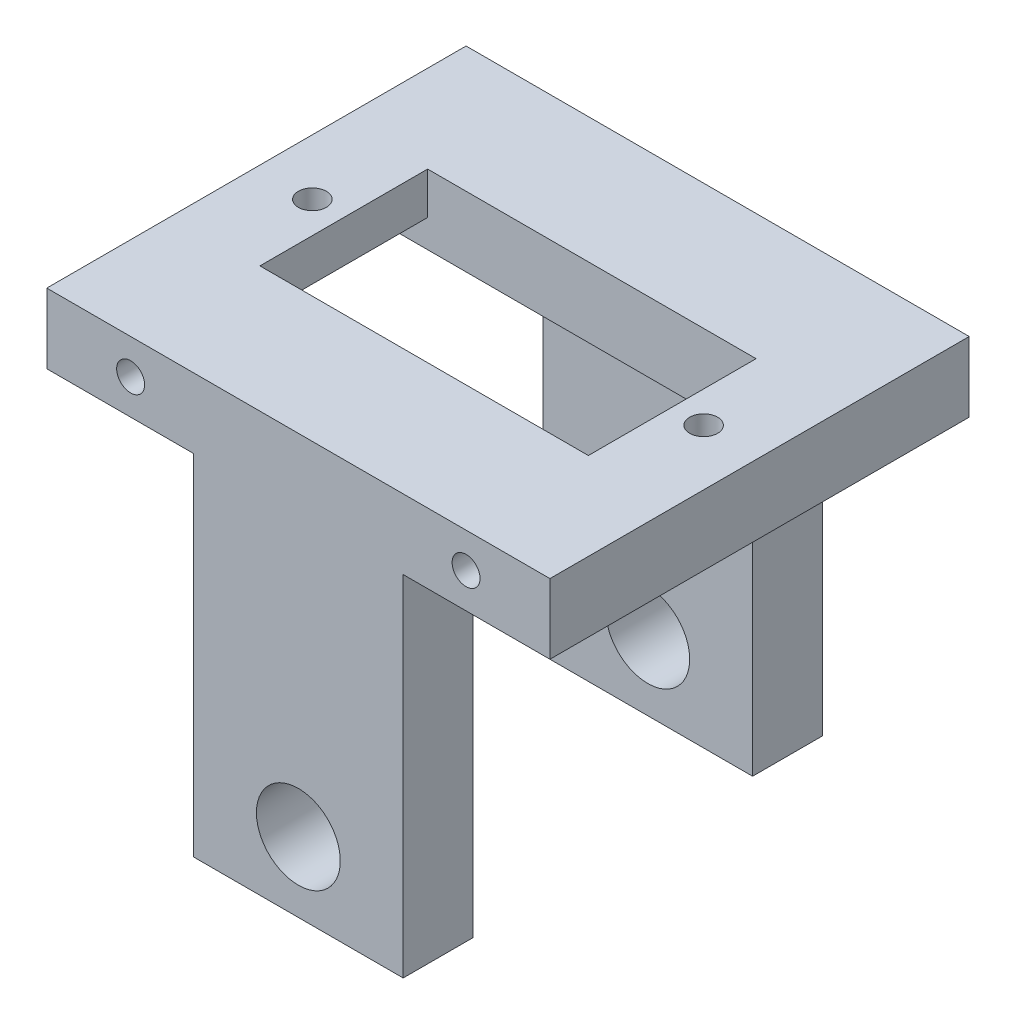
SolidWorks part; units mm, degrees
ref_plane "前视基准面" through (0, 0, 0) normal (0, 0, 1) x (1, 0, 0)
ref_plane "上视基准面" through (0, 0, 0) normal (0, 1, 0) x (1, 0, 0)
ref_plane "右视基准面" through (0, 0, 0) normal (1, 0, 0) x (0, 0, -1)
sketch "草图1" plane through (0, 0, 0) normal (0, 1, 0) x (1, 0, 0)
  line L1 (-18, 15) -> (18, 15)
  line L2 (-18, 15) -> (-18, -15)
  line L3 (-18, -15) -> (18, -15)
  line L4 (18, 15) -> (18, -15)
  line L5 (-18, 15) -> (18, -15) construction
  line L6 (-18, -15) -> (18, 15) construction
  point P0 (0, 0)
  dimension "D1" = 30
  dimension "D2" = 36
extrude "凸台-拉伸1" add sketch "草图1" along normal blind 5
sketch "草图4" plane through (0, 0, 0) normal (0, -1, 0) x (1, 0, 0)
  line L1 (-16.5, 6) -> (16.5, 6)
  line L2 (-16.5, 6) -> (-16.5, -6)
  line L3 (-16.5, -6) -> (16.5, -6)
  line L4 (16.5, 6) -> (16.5, -6)
  line L5 (-16.5, 6) -> (16.5, -6) construction
  line L6 (-16.5, -6) -> (16.5, 6) construction
  point P0 (0, 0)
  dimension "D1" = 33
  dimension "D2" = 12
extrude "切除-拉伸2" cut sketch "草图4" against normal blind 2
sketch "草图8" plane through (0, 2, 0) normal (0, -1, 0) x (1, 0, 0)
  line L0 (0, -1000) -> (0, 49000) construction
  circle A0 centre (14, 0) radius 1
  circle A1 centre (-14, 0) radius 1
  dimension "D1" = 28
  dimension "D2" = 2
extrude "切除-拉伸6" cut sketch "草图8" against normal blind 3
sketch "草图5" plane through (0, 2, 0) normal (0, -1, 0) x (1, 0, 0)
  line L0 (16.5, 6) -> (-16.5, 6) construction
  line L1 (-11.75, -6) -> (11.75, -6)
  line L2 (-11.75, -6) -> (-11.75, 6)
  line L3 (-11.75, 6) -> (11.75, 6)
  line L4 (11.75, -6) -> (11.75, 6)
  line L5 (-11.75, -6) -> (11.75, 6) construction
  line L6 (-11.75, 6) -> (11.75, -6) construction
  point P0 (0, 0)
  dimension "D1" = 23.5
extrude "切除-拉伸3" cut sketch "草图5" against normal up to surface (3 mm away) and the other way through all up to face at (-14, 5, -1)
sketch "草图9" plane through (0, 0, -15) normal (0, 0, -1) x (-1, 0, 0)
  line L0 (-1000, 2.5) -> (49000, 2.5) construction
  line L2 (-18, 5) -> (18, 0) construction
  line L3 (18, 5) -> (-18, 0) construction
  line L4 (0, -997.25) -> (0, 49002.75) construction
  circle A0 centre (12, 2.5) radius 1
  circle A1 centre (-12, 2.5) radius 1
  point P7 (0, 2.5)
  dimension "D1" = 2
  dimension "D2" = 12
extrude "切除-拉伸7" cut sketch "草图9" against normal blind 5
mirror "镜向1" about plane through (0, 0, 0) normal (0, 0, 1) of "切除-拉伸7"
sketch "草图11" plane through (0, 0, 0) normal (0, -1, 0) x (1, 0, 0)
  line L0 (0, 15) -> (0, 3.8777) construction
  line L2 (18, 0) -> (9.4315, 0) construction
  line L4 (-18, 15) -> (18, 15) construction
  line L5 (-7.5, 15) -> (7.5, 15)
  line L6 (-7.5, 15) -> (-7.5, 10)
  line L7 (-7.5, 10) -> (7.5, 10)
  line L8 (7.5, 15) -> (7.5, 10)
  line L9 (-7.5, 15) -> (7.5, 10) construction
  line L10 (-7.5, 10) -> (7.5, 15) construction
  line L11 (-7.5, -10) -> (7.5, -10)
  line L12 (7.5, -15) -> (7.5, -10)
  line L13 (-7.5, -15) -> (7.5, -15)
  line L14 (-7.5, -15) -> (-7.5, -10)
  point P2 (0, 12.5)
  dimension "D1" = 15
  dimension "D2" = 5
extrude "凸台-拉伸3" add sketch "草图11" along normal blind 25
sketch "草图12" plane through (0, 0, -15) normal (0, 0, -1) x (-1, 0, 0)
  line L0 (0, -25) -> (0, -16.5748) construction
  line L1 (7.5, -25) -> (-7.5, -25) construction
  circle A0 centre (0, -20) radius 3
  point P7 (0, -18.0236)
  dimension "D1" = 6
  dimension "D2" = 5
extrude "切除-拉伸8" cut sketch "草图12" against normal up to surface (30 mm away) up to face at (13, 2.5, 15)
